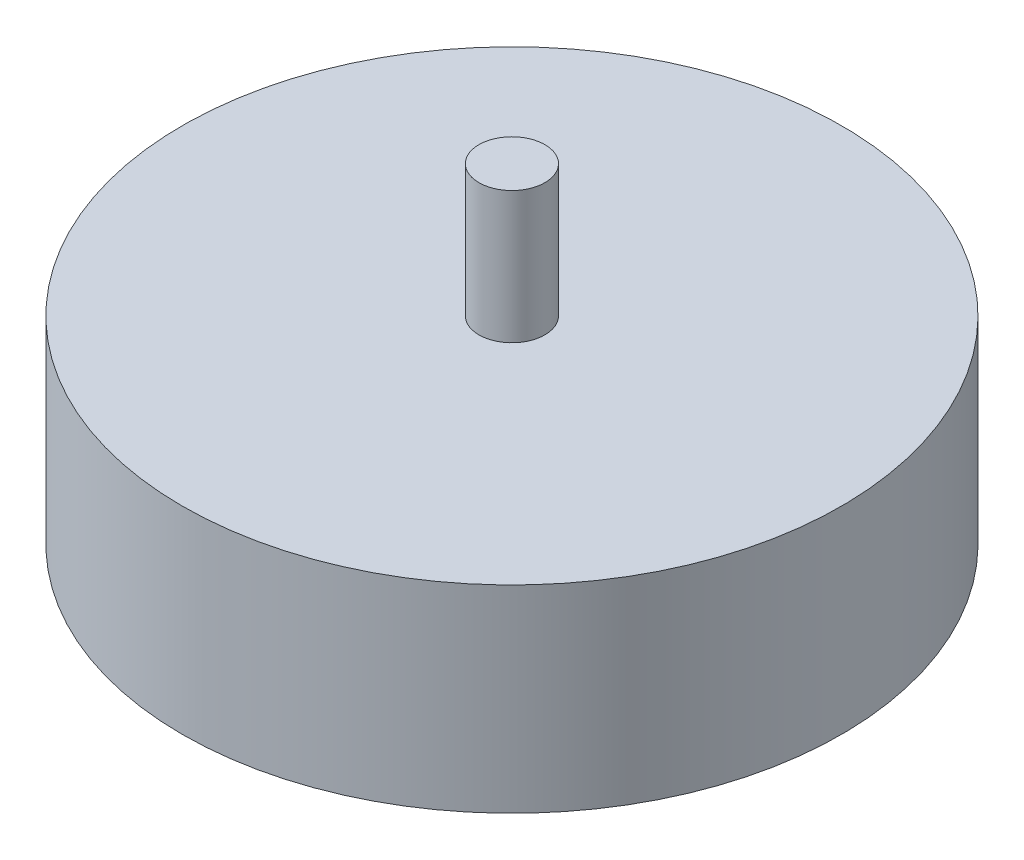
SolidWorks part; units mm, degrees
ref_plane "Front" through (0, 0, 0) normal (0, 0, 1) x (1, 0, 0)
ref_plane "Top" through (0, 0, 0) normal (0, 1, 0) x (1, 0, 0)
ref_plane "Right" through (0, 0, 0) normal (1, 0, 0) x (0, 0, -1)
sketch "Sketch1" plane through (0, 0, 0) normal (0, 1, 0) x (1, 0, 0)
  circle A0 centre (0, 0) radius 25
  dimension "D1" = 50
extrude "Boss-Extrude1" add sketch "Sketch1" along normal blind 15
sketch "Sketch2" plane through (0, 0, 0) normal (0, -1, 0) x (1, 0, 0)
  circle A0 centre (0, 0) radius 4
  dimension "D1" = 8
extrude "Cut-Extrude1" cut sketch "Sketch2" against normal blind 1
sketch "Sketch3" plane through (0, 15, 0) normal (0, 1, 0) x (1, 0, 0)
  circle A0 centre (0, 0) radius 2.5
  dimension "D1" = 5
extrude "Boss-Extrude2" add sketch "Sketch3" along normal blind 10
